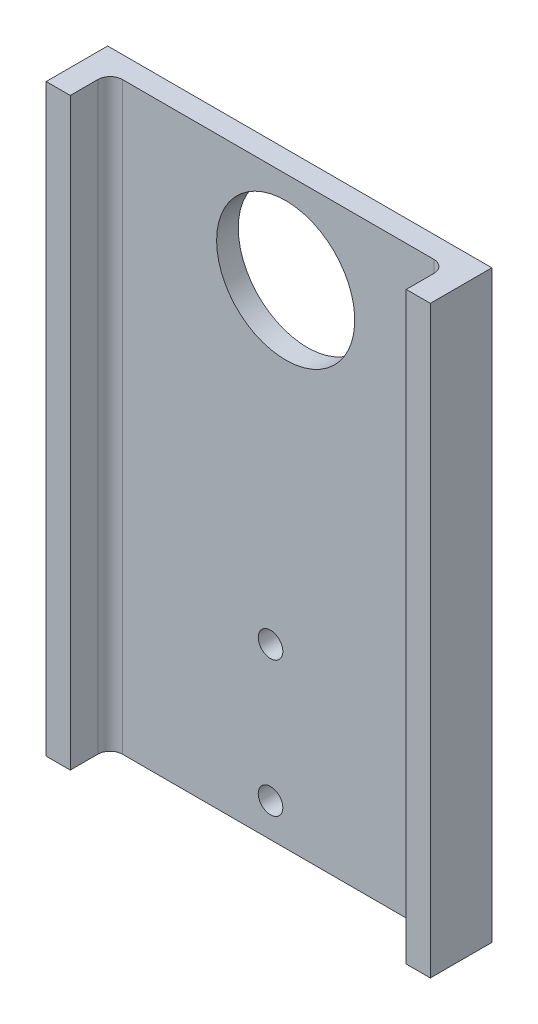
SolidWorks part; units mm, degrees
material "6061 Alloy"
ref_plane "Front Plane" through (0, 0, 0) normal (0, 0, 1) x (1, 0, 0)
ref_plane "Top Plane" through (0, 0, 0) normal (0, 1, 0) x (1, 0, 0)
ref_plane "Right Plane" through (0, 0, 0) normal (1, 0, 0) x (0, 0, -1)
sketch "Sketch2" plane through (0, 0, 0) normal (0, 1, 0) x (1, 0, 0)
  line L0 (0, 0) -> (41.2265, 0)
  line L1 (41.2265, 0) -> (41.2265, -12.7)
  line L2 (41.2265, -12.7) -> (36.2481, -12.7)
  line L3 (36.2481, -12.7) -> (36.2481, -4.4704)
  line L4 (36.2481, -4.4704) -> (0, -4.4704)
  line L5 (0, -4.4704) -> (-33.1216, -4.4704)
  line L6 (-33.1216, -4.4704) -> (-33.1216, -12.7)
  line L7 (-33.1216, -12.7) -> (-38.1, -12.7)
  line L8 (-38.1, -12.7) -> (-38.1, 0)
  line L9 (-38.1, 0) -> (0, 0)
  point P9 (0, 0)
extrude "Boss-Extrude1" add sketch "Sketch2" along normal blind 120.65
sketch "Sketch3" plane through (0, 0, 0) normal (0, 0, -1) x (-1, 0, 0)
  line L0 (-41.2265, 0) -> (38.1, 0) construction
  line L1 (-41.2265, 120.65) -> (-41.2265, 0) construction
  circle A0 centre (-3.1265, 101.6) radius 14.2621
  dimension "D1" = 101.6
  dimension "D2" = 38.1
extrude "Cut-Extrude1" cut sketch "Sketch3" against normal blind 107.95
sketch "Sketch4" plane through (0, 0, 0) normal (0, 0, -1) x (-1, 0, 0)
  circle A0 centre (0, 34.925) radius 2.54
  circle A1 centre (-3.1265, 101.6) radius 14.2621 construction
  dimension "D1" = 66.675
extrude "Cut-Extrude2" cut sketch "Sketch4" against normal blind 127 contours A0
sketch "Sketch5" plane through (0, 0, 0) normal (0, 0, -1) x (-1, 0, 0)
  circle A0 centre (0, 6.985) radius 2.54
  circle A1 centre (0, 34.925) radius 2.54 construction
  dimension "D1" = 27.94
extrude "Cut-Extrude3" cut sketch "Sketch5" against normal blind 127
fillet "Fillet1" radius 2.54 1 edges at (-33.1216, 60.325, 4.4704)
fillet "Fillet2" radius 2.54 1 edges at (36.2481, 60.325, 4.4704)
